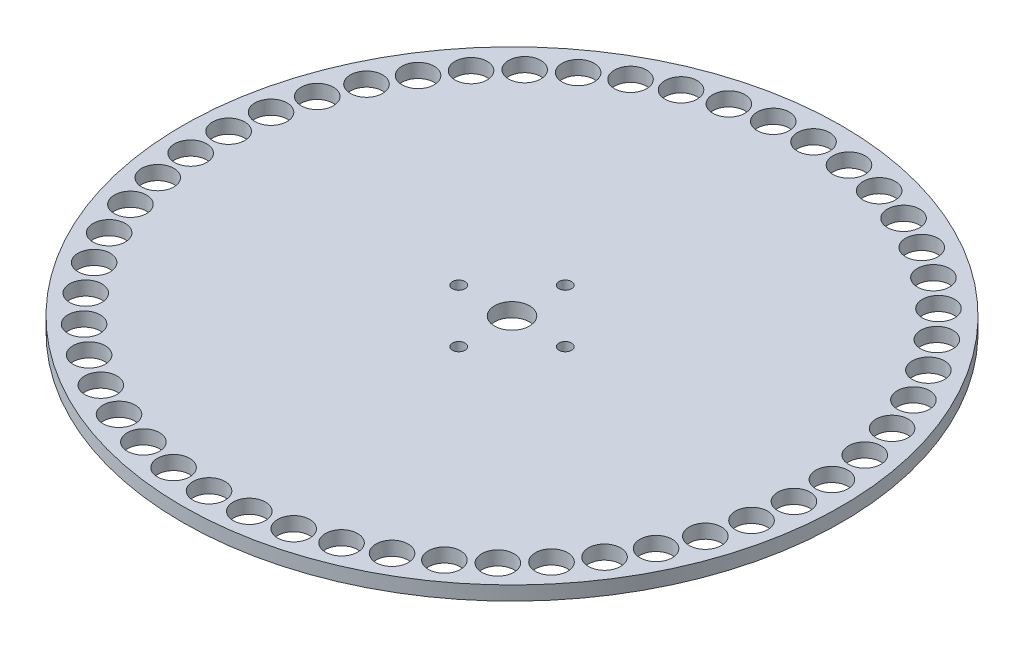
SolidWorks part; units mm, degrees
ref_plane "Front Plane" through (0, 0, 0) normal (0, 0, 1) x (1, 0, 0)
ref_plane "Top Plane" through (0, 0, 0) normal (0, 1, 0) x (1, 0, 0)
ref_plane "Right Plane" through (0, 0, 0) normal (1, 0, 0) x (0, 0, -1)
sketch "Sketch1" plane through (0, 0, 0) normal (0, 1, 0) x (1, 0, 0)
  circle A0 centre (0, 0) radius 117.5
  dimension "D1" = 235
extrude "Boss-Extrude1" add sketch "Sketch1" along normal blind 5
sketch "Sketch2" plane through (0, 5, 0) normal (0, 1, 0) x (1, 0, 0)
  circle A0 centre (0, 0) radius 107.5 construction
  circle A1 centre (0, 107.5) radius 5.75
  dimension "D1" = 215
  dimension "D2" = 11.5
extrude "Cut-Extrude1" cut sketch "Sketch2" against normal through all
pattern_circular "CirPattern1" count 50 over 360 about axis through (0, 0, 0.2581) along (0, 1, 0) of "Cut-Extrude1"
sketch "Sketch3" plane through (0, 5, 0) normal (0, 1, 0) x (1, 0, 0)
  circle A0 centre (0, 0) radius 6.25
  dimension "D1" = 12.5
extrude "Cut-Extrude2" cut sketch "Sketch3" against normal through all
sketch "Sketch4" plane through (0, 5, 0) normal (0, 1, 0) x (1, 0, 0)
  circle A0 centre (19, 0) radius 2.25
  dimension "D1" = 4.5
  dimension "D2" = 19
extrude "Cut-Extrude3" cut sketch "Sketch4" against normal through all
pattern_circular "CirPattern2" count 4 over 360 about axis through (0, 0, 0) along (0, 1, 0) of "Cut-Extrude3"
